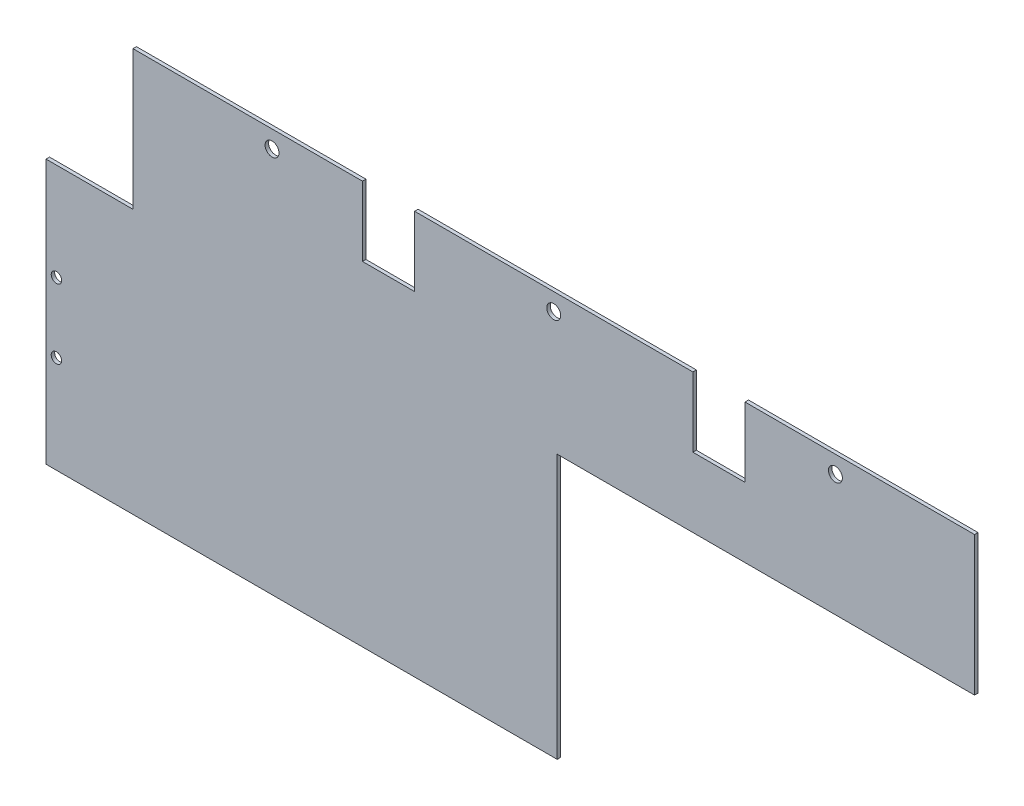
SolidWorks part; units mm, degrees
material "Thornel Mat VMA"
ref_plane "前视基准面" through (0, 0, 0) normal (0, 0, 1) x (1, 0, 0)
ref_plane "上视基准面" through (0, 0, 0) normal (0, 1, 0) x (1, 0, 0)
ref_plane "右视基准面" through (0, 0, 0) normal (1, 0, 0) x (0, 0, -1)
sketch "草图1" plane through (0, 0, 0) normal (0, 0, 1) x (1, 0, 0)
  line L0 (0, 0) -> (0, 76)
  line L1 (0, 76) -> (25, 76)
  line L2 (25, 76) -> (25, 116)
  line L3 (25, 116) -> (267, 116)
  line L4 (267, 116) -> (267, 76)
  line L5 (267, 76) -> (292, 76)
  line L6 (292, 76) -> (292, 0)
  line L7 (292, 0) -> (0, 0)
  line L8 (3, 48) -> (3, 28) construction
  line L9 (0, 38) -> (292, 38) construction
  line L10 (146, 116) -> (146, 0) construction
  line L11 (289, 48) -> (289, 28) construction
  circle A0 centre (3, 48) radius 1.5
  circle A1 centre (3, 28) radius 1.5
  circle A2 centre (289, 28) radius 1.5
  circle A3 centre (289, 48) radius 1.5
  point P13 (3, 38)
  dimension "D7" = 3
  dimension "D1" = 292
  dimension "D2" = 76
  dimension "D3" = 40
  dimension "D4" = 25
  dimension "D5" = 20
  dimension "D6" = 3
extrude "凸台-拉伸1" add sketch "草图1" along normal blind 1
sketch "草图2" plane through (0, 0, 1) normal (0, 0, 1) x (1, 0, 0)
  line L0 (146, 116) -> (146, 0) construction
  line L1 (267, 116) -> (25, 116) construction
  line L2 (0, 0) -> (292, 0) construction
  line L3 (186, 116) -> (186, 96)
  line L4 (91, 116) -> (106, 116)
  line L5 (91, 116) -> (91, 96)
  line L6 (91, 96) -> (106, 96)
  line L7 (106, 116) -> (106, 96)
  line L8 (201, 96) -> (186, 96)
  line L9 (201, 116) -> (201, 96)
  line L10 (201, 116) -> (186, 116)
  line L11 (25, 116) -> (25, 76) construction
  circle A0 centre (65, 111) radius 2
  circle A1 centre (227, 111) radius 2
  circle A2 centre (146, 111) radius 2
  point P14 (98.5, 116)
  point P15 (193.5, 116)
  dimension "D4" = 4
  dimension "D7" = 4
  dimension "D1" = 95
  dimension "D2" = 15
  dimension "D3" = 20
  dimension "D5" = 5
  dimension "D6" = 40
extrude "切除-拉伸1" cut sketch "草图2" against normal through all
sketch "草图3" plane through (0, 0, 1) normal (0, 0, 1) x (1, 0, 0)
  line L0 (292, 76) -> (267, 76) construction
  line L1 (292, 0) -> (147, 0)
  line L2 (292, 0) -> (292, 76)
  line L3 (292, 76) -> (147, 76)
  line L4 (147, 0) -> (147, 76)
  line L5 (292, 0) -> (292, 76) construction
  dimension "D1" = 145
extrude "切除-拉伸2" cut sketch "草图3" against normal through all
